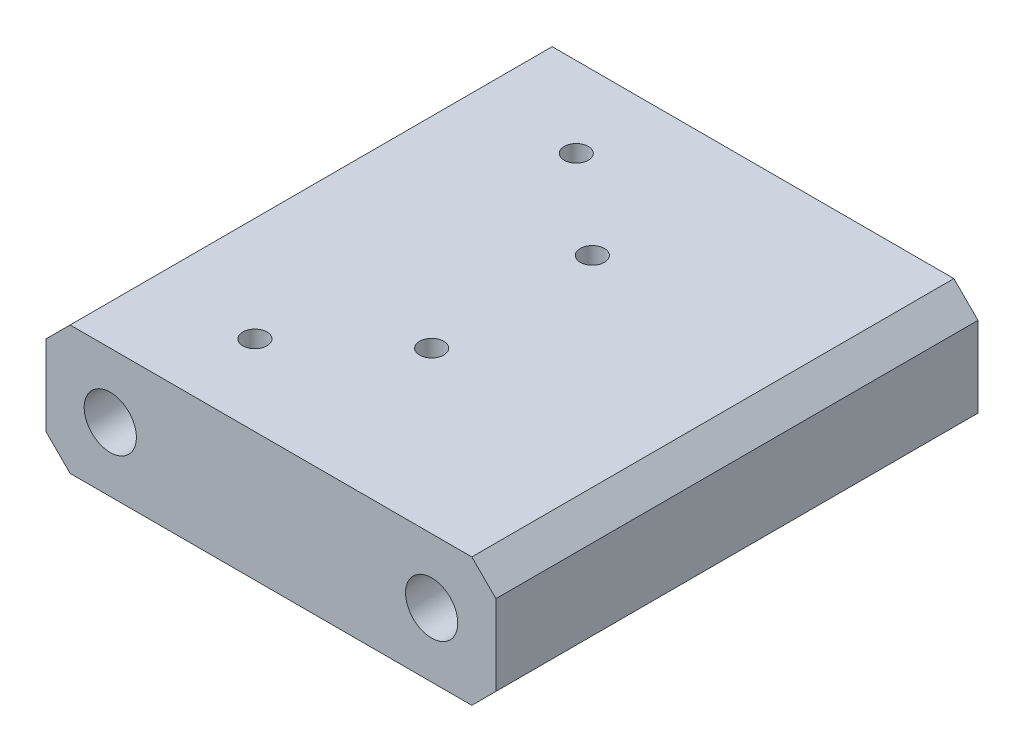
SolidWorks part; units mm, degrees
ref_plane "前基準面" through (0, 0, 0) normal (0, 0, 1) x (1, 0, 0)
ref_plane "上基準面" through (0, 0, 0) normal (0, 1, 0) x (1, 0, 0)
ref_plane "右基準面" through (0, 0, 0) normal (1, 0, 0) x (0, 0, -1)
sketch "草圖1" plane through (0, 0, 0) normal (0, 1, 0) x (1, 0, 0)
  line L1 (0, 0) -> (50, 0)
  line L2 (0, 0) -> (0, 60)
  line L3 (0, 60) -> (50, 60)
  line L4 (50, 0) -> (50, 60)
  dimension "D1" = 60
  dimension "D2" = 50
extrude "填料-伸長1" add sketch "草圖1" along normal blind 16 contours L2 L3 L4 L1
sketch "草圖2" plane through (0, 0, -60) normal (0, 0, -1) x (-1, 0, 0)
  line L0 (0, 0) -> (-50, 0) construction
  line L1 (0, 16) -> (0, 0) construction
  circle A0 centre (-45, 8) radius 3.25
  circle A1 centre (-5, 8) radius 3.25
  dimension "D5" = 6.5
  dimension "D1" = 40
  dimension "D2" = 8
  dimension "D3" = 8
  dimension "D4" = 5
extrude "除料-伸長1" cut sketch "草圖2" against normal blind 100
sketch "草圖3" plane through (0, 16, 0) normal (0, 1, 0) x (1, 0, 0)
  line L0 (25, 0) -> (25, 60) construction
  line L1 (0, 0) -> (50, 0) construction
  line L2 (0, 60) -> (50, 60) construction
  circle A0 centre (13, 10) radius 1.5
  circle A1 centre (13, 50) radius 1.5
  point P10 (16.514, 10)
  point P11 (0, 0)
  dimension "D5" = 3
  dimension "D1" = 12
  dimension "D2" = 12
  dimension "D3" = 10
  dimension "D4" = 10
extrude "除料-伸長2" cut sketch "草圖3" against normal blind 100
sketch "草圖4" plane through (0, 0, 0) normal (0, 0, 1) x (1, 0, 0)
  line L0 (0, 0) -> (-3, 3)
  line L1 (-3, 3) -> (-3, 13)
  line L2 (-3, 13) -> (0, 16)
  line L3 (0, 16) -> (0, 0)
  line L4 (-3, 8) -> (0, 8) construction
  line L5 (25, 0) -> (25, 16) construction
  line L6 (0, 0) -> (50, 0) construction
  line L7 (0, 16) -> (50, 16) construction
  line L8 (53, 13) -> (50, 16)
  line L9 (50, 16) -> (50, 0)
  line L10 (50, 0) -> (53, 3)
  line L11 (53, 3) -> (53, 13)
  dimension "D1" = 3
  dimension "D2" = 10
extrude "填料-伸長2" add sketch "草圖4" against normal blind 60
sketch "草圖5" plane through (0, 16, 0) normal (0, 1, 0) x (1, 0, 0)
  line L0 (25, 0) -> (25, 60) construction
  line L3 (0, 0) -> (50, 0) construction
  line L4 (0, 60) -> (50, 60) construction
  circle A0 centre (25, 20) radius 1.5
  circle A1 centre (25, 40) radius 1.5
  point P10 (0, 0)
  point P12 (25, 11.7786)
  dimension "D3" = 3
  dimension "D1" = 20
  dimension "D2" = 20
extrude "除料-伸長3" cut sketch "草圖5" against normal blind 60
